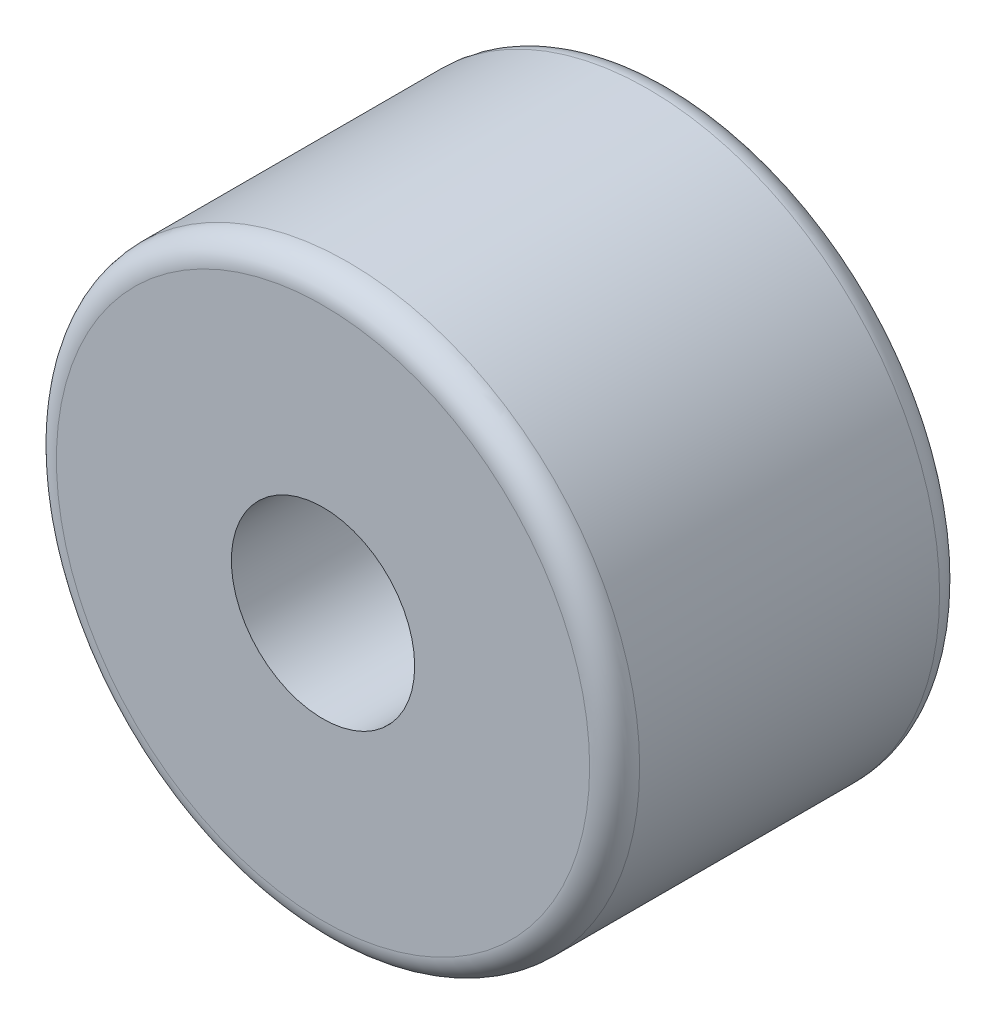
SolidWorks part; units mm, degrees
ref_plane "Front Plane" through (0, 0, 0) normal (0, 0, 1) x (1, 0, 0)
ref_plane "Top Plane" through (0, 0, 0) normal (0, 1, 0) x (1, 0, 0)
ref_plane "Right Plane" through (0, 0, 0) normal (1, 0, 0) x (0, 0, -1)
sketch "Sketch1" plane through (0, 0, 0) normal (0, 0, 1) x (1, 0, 0)
  circle A0 centre (0, 0) radius 35
  dimension "D1" = 70
extrude "Boss-Extrude1" add sketch "Sketch1" along normal blind 42
fillet "Fillet1" radius 3 2 edges at (35, 0, 42) (35, 0, 0)
sketch "Sketch2" plane through (0, 0, 42) normal (0, 0, 1) x (1, 0, 0)
  line L0 (-29.5816, 12.2036) -> (29.5816, -12.2036) construction
  circle A0 centre (0, 0) radius 11
  circle A1 centre (0, 0) radius 32 construction
  point P2 (0, 0)
  point P7 (0, 0)
  dimension "D1" = 22
extrude "Cut-Extrude1" cut sketch "Sketch2" against normal through all
